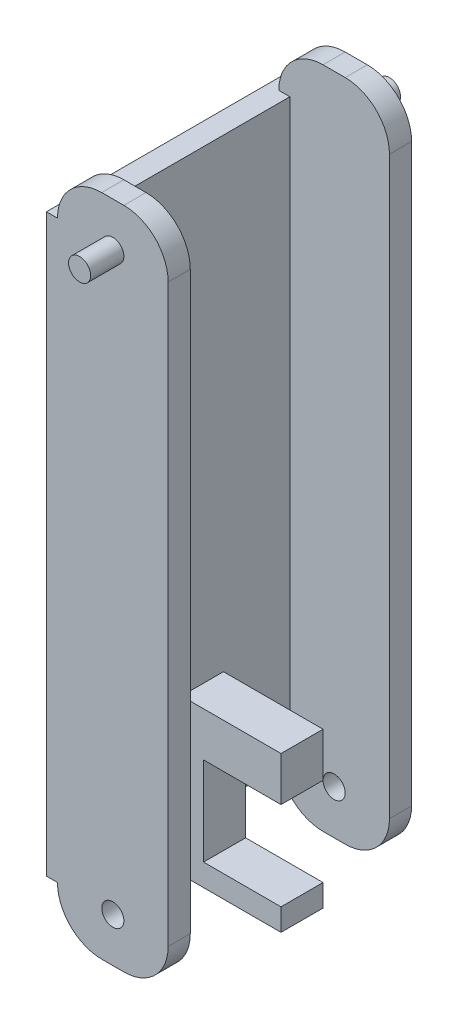
SolidWorks part; units mm, degrees
ref_plane "Front Plane" through (0, 0, 0) normal (0, 0, 1) x (1, 0, 0)
ref_plane "Top Plane" through (0, 0, 0) normal (0, 1, 0) x (1, 0, 0)
ref_plane "Right Plane" through (0, 0, 0) normal (1, 0, 0) x (0, 0, -1)
sketch "Sketch1" plane through (0, 0, 0) normal (0, 0, 1) x (1, 0, 0)
  line L0 (0, 7.8092) -> (0, -7.5836) construction
  line L1 (-16.5434, 0) -> (17.7066, 0) construction
  line L2 (-5, -20) -> (5, -20)
  line L6 (0, 7.8092) -> (0, 18.1168) construction
  line L7 (-25, 0) -> (-25, 260)
  line L8 (-5, 280) -> (5, 280)
  line L9 (25, 260) -> (25, 0)
  line L10 (0, 332.7621) -> (0, -24.8778) construction
  arc A0 (5, -20) -> (25, 0) centre (5, 0) ccw
  arc A1 (-5, -20) -> (-25, 0) centre (-5, 0) cw
  circle A2 centre (0, 0) radius 5
  arc A3 (5, 280) -> (25, 260) centre (5, 260) cw
  arc A4 (-25, 260) -> (-5, 280) centre (-5, 260) cw
  point P14 (25, -20)
  point P17 (-25, -20)
  point P22 (25, 280)
  dimension "D4" = 20
  dimension "D5" = 20
  dimension "D6" = 20
  dimension "D1" = 50
  dimension "D2" = 25
  dimension "D3" = 300
extrude "Boss-Extrude1" add sketch "Sketch1" along normal blind 10
sketch "Sketch2" plane through (0, 0, 10) normal (0, 0, 1) x (1, 0, 0)
  line L0 (0, 310.2932) -> (0, -54.3198) construction
  line L1 (5, 280) -> (-5, 280) construction
  circle A1 centre (0, 260) radius 5
  dimension "D1" = 20
  dimension "D2" = 10
extrude "Boss-Extrude2" add sketch "Sketch2" along normal blind 15
sketch "Sketch3" plane through (0, 0, 0) normal (0, 0, -1) x (-1, 0, 0)
  line L0 (0, -108.7365) -> (0, 392.6868) construction
  line L1 (25, 0) -> (20, 0)
  line L2 (20, 0) -> (20, 260)
  line L3 (20, 260) -> (25, 260)
  line L4 (25, 260) -> (25, 0)
  dimension "D1" = 260
  dimension "D2" = 260
  dimension "D3" = 5
  dimension "D4" = 20
extrude "Boss-Extrude3" add sketch "Sketch3" along normal blind 45
mirror "Mirror1" about plane through (0, 0, -45) normal (0, 0, 1) of "Boss-Extrude3", "Boss-Extrude2", "Boss-Extrude1"
sketch "Sketch8" plane through (0, 0, 0) normal (0, -1, 0) x (1, 0, 0)
  line L0 (-25, -41) -> (-20, -41)
  line L2 (-25, -90) -> (-25, 0) construction
  line L3 (-20, -90) -> (-20, 0) construction
  line L4 (-20, -41) -> (-20, -60)
  line L5 (-20, -60) -> (-25, -60)
  line L6 (-25, -60) -> (-25, -41)
  line L7 (-20, 0) -> (-25, 0) construction
  line L8 (-5, -90) -> (-25, -90) construction
  dimension "D1" = 41
  dimension "D2" = 19
  dimension "D3" = 30
extrude "Boss-Extrude4" add sketch "Sketch8" along normal blind 20
sketch "Sketch9" plane through (-20, 0, 0) normal (1, 0, 0) x (0, 0, -1)
  line L0 (41, -20) -> (41, -10)
  line L1 (41, -20) -> (41, 0) construction
  line L2 (41, -10) -> (60, -10)
  line L3 (60, -20) -> (60, 0) construction
  line L4 (60, -10) -> (60, -20)
  line L5 (60, -20) -> (41, -20)
  line L6 (41, 286.5383) -> (41, -36.1632) construction
  line L7 (60, 286.5383) -> (60, -36.1632) construction
  line L8 (60, 30) -> (41, 30)
  line L9 (41, 30) -> (41, 50)
  line L10 (41, 50) -> (60, 50)
  line L11 (60, 50) -> (60, 30)
  dimension "D1" = 10
  dimension "D2" = 40
  dimension "D3" = 20
extrude "Boss-Extrude5" add sketch "Sketch9" along normal blind 45
sketch "Sketch10" plane through (-20, 0, 0) normal (1, 0, 0) x (0, 0, -1)
  line L0 (41, 30) -> (41, -10)
  line L1 (41, -10) -> (60, -10)
  line L2 (60, -10) -> (60, 30)
  line L3 (60, 30) -> (41, 30)
extrude "Boss-Extrude6" add sketch "Sketch10" along normal blind 10
sketch "Sketch11" plane through (-25, 0, 0) normal (-1, 0, 0) x (0, 0, 1)
  line L0 (10, 0) -> (-41, 0)
  line L1 (-41, 0) -> (-41, -20)
  line L2 (-41, -20) -> (-60, -20)
  line L3 (-60, -20) -> (-60, 0)
  line L4 (-60, 0) -> (-100, 0)
  line L5 (-100, 0) -> (-100, 260)
  line L6 (-100, 265) -> (-100, 255) construction
  line L7 (-100, 260) -> (10, 260)
  line L8 (10, 255) -> (10, 265) construction
  line L9 (10, 260) -> (10, 0)
extrude "Boss-Extrude7" add sketch "Sketch11" along normal blind 5
